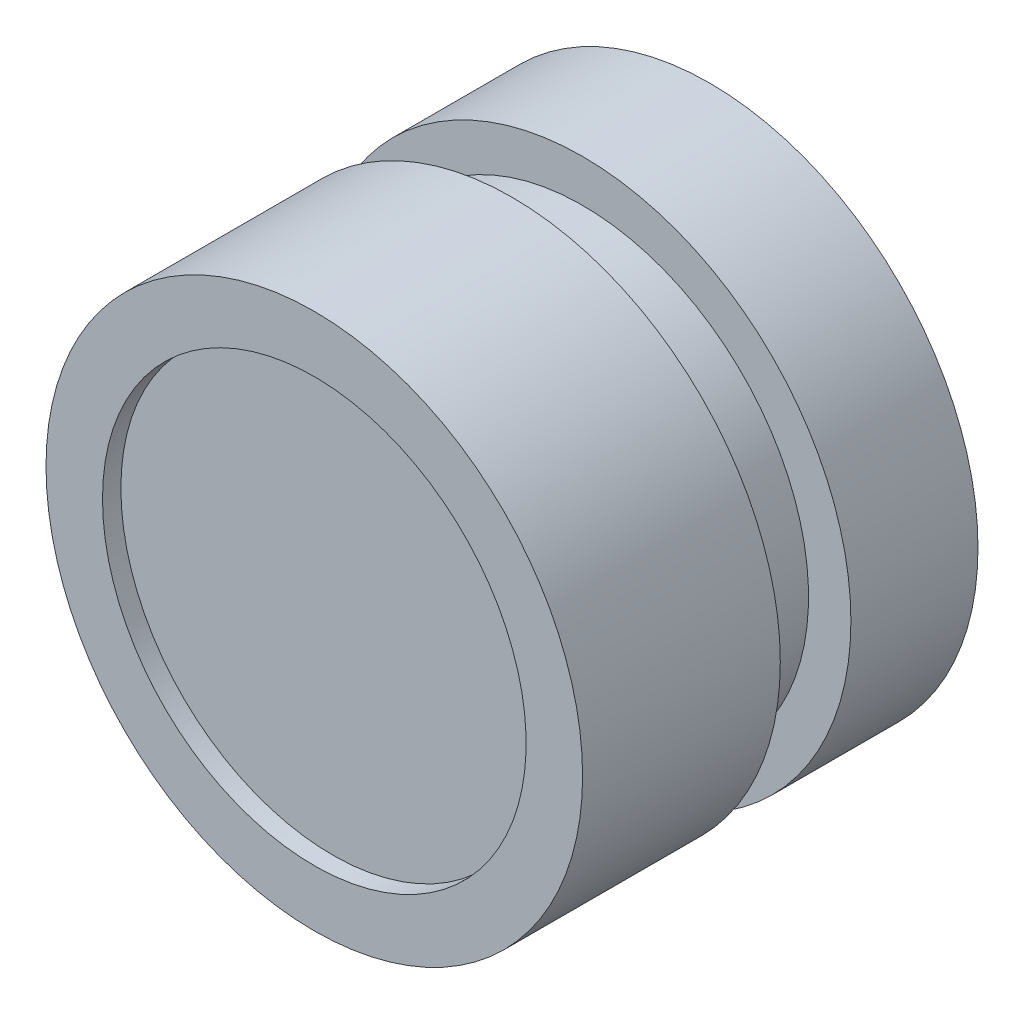
SolidWorks part; units mm, degrees
material "AISI 304"
ref_plane "Спереди" through (0, 0, 0) normal (0, 0, 1) x (1, 0, 0)
ref_plane "Сверху" through (0, 0, 0) normal (0, 1, 0) x (1, 0, 0)
ref_plane "Справа" through (0, 0, 0) normal (1, 0, 0) x (0, 0, -1)
other "Configuration Table"
sketch "Эскиз2" plane through (0, 0, 0) normal (0, 1, 0) x (1, 0, 0)
  line L0 (0, 0) -> (9.5, 0) construction
  line L1 (9.5, 0) -> (9.5, 14) construction
  line L2 (9.5, 14) -> (0, 14) construction
  line L3 (0, 14) -> (0, 0) construction
  line L4 (0, 14) -> (0, 0.6509)
  line L5 (0, 14) -> (9.5, 14)
  line L6 (9.5, 14) -> (9.5, 9.5)
  line L7 (9.5, 9.5) -> (8, 9.5)
  line L8 (8, 9.5) -> (8, 7)
  line L9 (8, 7) -> (9.5, 7)
  line L10 (9.5, 7) -> (9.5, 0)
  line L11 (9.5, 0) -> (7.5, 0)
  line L12 (7.5, 0) -> (7.5, 0.6509)
  line L13 (7.5, 0.6509) -> (0, 0.6509)
  dimension "D1" = 9.5
  dimension "D2" = 14
  dimension "D3" = 1.5
  dimension "D4" = 2.5
  dimension "D5" = 2
revolve "Повернуть1" add sketch "Эскиз2" angle 360 about L4
